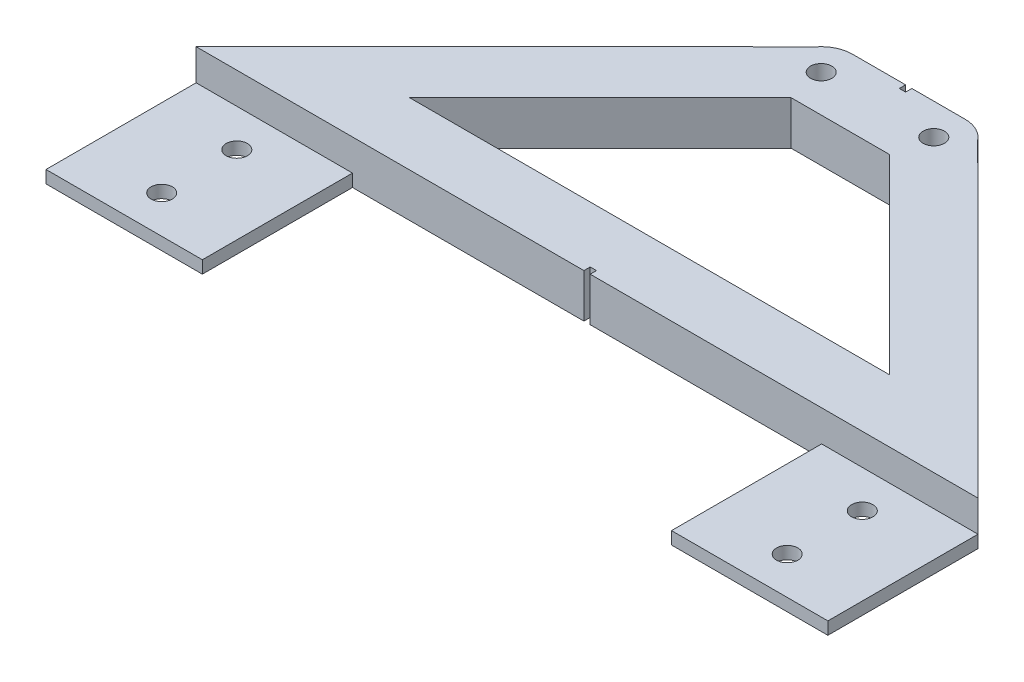
SolidWorks part; units mm, degrees
ref_plane "Front Plane" through (0, 0, 0) normal (0, 0, 1) x (1, 0, 0)
ref_plane "Top Plane" through (0, 0, 0) normal (0, 1, 0) x (1, 0, 0)
ref_plane "Right Plane" through (0, 0, 0) normal (1, 0, 0) x (0, 0, -1)
sketch "Triangle" plane through (0, 0, 0) normal (0, 1, 0) x (1, 0, 0)
  line L0 (0, 0) -> (125, 0)
  line L1 (125, 0) -> (82.5, 42.5)
  line L2 (42.5, 42.5) -> (0, 0)
  line L3 (62.5, 0) -> (62.5, 42.5) construction
  line L4 (82.5, 42.5) -> (42.5, 42.5)
  line L5 (24.1421, 10) -> (100.8579, 10)
  line L6 (100.8579, 10) -> (70.3579, 40.5)
  line L7 (70.3579, 40.5) -> (54.6421, 40.5)
  line L8 (54.6421, 40.5) -> (24.1421, 10)
  dimension "D1" = 125
  dimension "D2" = 40
  dimension "D3" = 45
  dimension "D4" = 45
  dimension "D5" = 10
  dimension "D6" = 2
  dimension "D7" = 10
  dimension "D8" = 45
  dimension "D9" = 10
  dimension "D10" = 45
sketch "Bearing Mounts" plane through (0, 0, 0) normal (0, 1, 0) x (1, 0, 0)
  line L0 (12.5, -24) -> (12.5, 0) construction
  line L1 (25, 0) -> (0, 0)
  line L2 (25, 0) -> (25, -24)
  line L3 (25, -24) -> (0, -24)
  line L4 (0, 0) -> (0, -24)
  line L5 (112.5, -24) -> (112.5, 0) construction
  line L6 (125, 0) -> (100, 0)
  line L7 (125, 0) -> (125, -24)
  line L8 (125, -24) -> (100, -24)
  line L9 (100, 0) -> (100, -24)
  line L10 (100, -24) -> (25, -24) construction
  line L11 (62.5, -24) -> (62.5, 68.4083) construction
  line L14 (62.5, 42.5) -> (62.5, -51.9511) construction
  dimension "D1" = 24
  dimension "D2" = 25
  dimension "D3" = 24
  dimension "D4" = 25
  dimension "D5" = 100
extrude "Bearing Mount Plates" add sketch "Bearing Mounts" along normal blind 2
extrude "Bridge" add sketch "Triangle" along normal blind 7
sketch "M3 Bearing Holes" plane through (0, 0, 0) normal (0, -1, 0) x (1, 0, 0)
  line L0 (125, 24) -> (125, 0) construction
  line L2 (125, 0) -> (82.5, -42.5) construction
  line L4 (100, 0) -> (100, 24) construction
  line L5 (0, 24) -> (25, 24) construction
  line L6 (0, 0) -> (125, 0) construction
  line L7 (25, 24) -> (25, 0) construction
  line L12 (100, 24) -> (125, 24) construction
  circle A0 centre (112.5, 6) radius 1.7
  circle A1 centre (112.5, 18) radius 1.7
  circle A2 centre (12.5, 6) radius 1.7
  circle A3 centre (12.5, 18) radius 1.7
  dimension "D1" = 3.4
  dimension "D5" = 6
  dimension "D10" = 3.4
  dimension "D2" = 6
  dimension "D3" = 12.5
  dimension "D4" = 6
  dimension "D6" = 12.5
  dimension "D7" = 12.5
  dimension "D8" = 6
  dimension "D9" = 12.5
extrude "Bearing Mount Holes" cut sketch "M3 Bearing Holes" against normal up to surface (2 mm away) up to face at (12.5, 2, 12)
sketch "Belt Mount" plane through (0, 0, 0) normal (0, -1, 0) x (1, 0, 0)
  line L1 (53.5, -41.4289) -> (71.5, -41.4289)
  line L2 (42.5, -42.5) -> (0, 0) construction
  line L3 (53.5, -51.4289) -> (71.5, -51.4289)
  line L4 (125, 0) -> (82.5, -42.5) construction
  arc A0 (53.5, -41.4289) -> (53.5, -51.4289) centre (53.5, -46.4289) ccw
  arc A1 (71.5, -51.4289) -> (71.5, -41.4289) centre (71.5, -46.4289) ccw
  dimension "D2" = 5
  dimension "D1" = 18
extrude "Belt Mount Plate" add sketch "Belt Mount" against normal blind 7
sketch "M3 Belt Holes" plane through (0, 0, 0) normal (0, -1, 0) x (1, 0, 0)
  circle A0 centre (53.5, -46.4289) radius 1.7
  circle A1 centre (71.5, -46.4289) radius 1.7
  dimension "D1" = 3.4
extrude "Belt Mount Screw Holes" cut sketch "M3 Belt Holes" against normal up to surface (7 mm away) up to face at (62.5, 7, -34.3824)
sketch "Sketch6" plane through (0, 0, 0) normal (0, -1, 0) x (1, 0, 0)
  line L0 (42.5, -42.5) -> (49.5, -49.4289)
  line L1 (49.5, -49.4289) -> (50.4075, -42.5)
  line L2 (50.4075, -42.5) -> (42.5, -42.5)
  line L3 (82.5, -42.5) -> (75.5, -49.4289)
  line L4 (75.5, -49.4289) -> (74.5925, -42.5)
  line L5 (74.5925, -42.5) -> (82.5, -42.5)
  line L6 (53.5, -49.4289) -> (94.0576, -49.4289) construction
  line L7 (94.0576, -49.4289) -> (23.5138, -49.4289) construction
  line L9 (53.5, -51.4289) -> (71.5, -51.4289) construction
  arc A0 (53.5, -41.4289) -> (53.5, -51.4289) centre (53.5, -46.4289) ccw construction
  arc A3 (71.5, -51.4289) -> (71.5, -41.4289) centre (71.5, -46.4289) ccw construction
  dimension "D1" = 2
extrude "Boss-Extrude1" add sketch "Sketch6" against normal up to surface (7 mm away) up to face at (71.5, 7, -48.1289)
sketch "Sketch7" plane through (0, 0, 0) normal (0, 0, 1) x (1, 0, 0)
  line L0 (62.5, 0) -> (62.5, 7)
  line L1 (0, 7) -> (125, 7) construction
  line L2 (24.1421, 0) -> (100.8579, 0) construction
  line L3 (62, 7) -> (63, 7)
  line L4 (62, 7) -> (62, 0)
  line L5 (62, 0) -> (63, 0)
  line L6 (63, 7) -> (63, 0)
  dimension "D1" = 0.5
  dimension "D2" = 0.5
extrude "Alignment helper 1" cut sketch "Sketch7" against normal blind 1 contours L4 L5 L6 L3
sketch "Sketch8" plane through (0, 0, -51.4289) normal (0, 0, -1) x (-1, 0, 0)
  line L0 (-62.5, 7) -> (-62.5, 0) construction
  line L1 (-53.5, 7) -> (-71.5, 7) construction
  line L2 (-53.5, 0) -> (-71.5, 0) construction
  line L4 (-62, 0) -> (-63, 0)
  line L5 (-62, 0) -> (-62, 7)
  line L6 (-62, 7) -> (-63, 7)
  line L7 (-63, 0) -> (-63, 7)
  dimension "D1" = 0.5
  dimension "D2" = 0.5
extrude "Alignment helper 2" cut sketch "Sketch8" against normal blind 1
